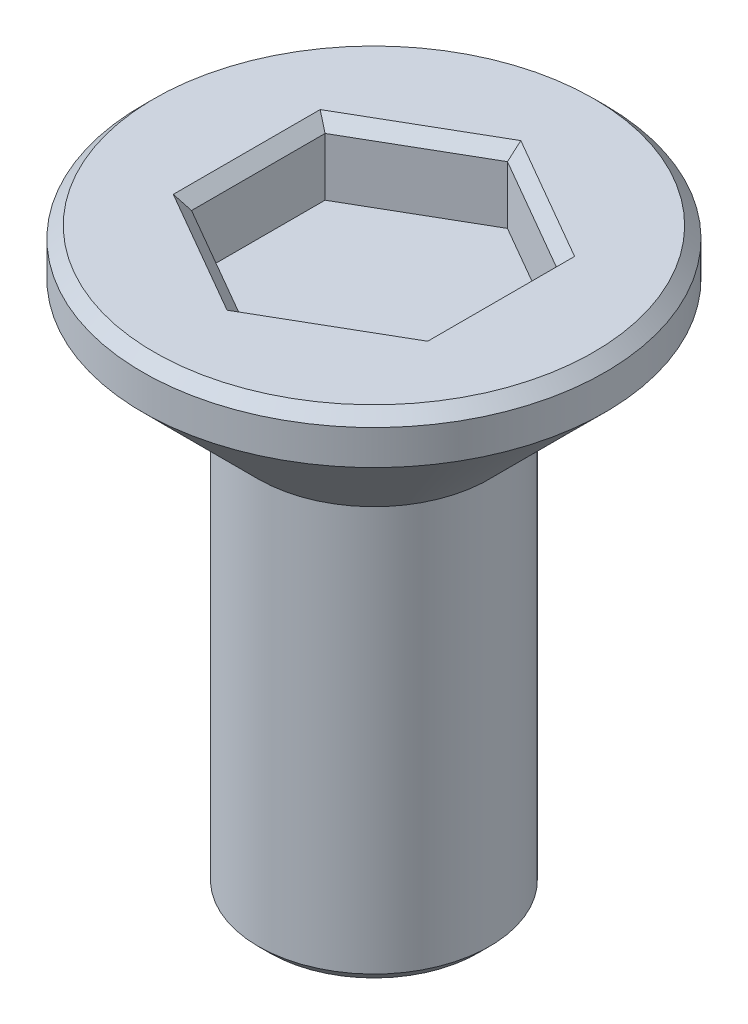
SolidWorks part; units mm, degrees
material "Plain Carbon Steel"
ref_plane "Front Plane" through (0, 0, 0) normal (0, 0, 1) x (1, 0, 0)
ref_plane "Top Plane" through (0, 0, 0) normal (0, 1, 0) x (1, 0, 0)
ref_plane "Right Plane" through (0, 0, 0) normal (1, 0, 0) x (0, 0, -1)
sketch "Sketch1" plane through (0, 0, 0) normal (1, 0, 0) x (0, 0, -1)
  line L0 (0, 0) -> (0, 5) construction
  line L1 (0, 5) -> (-2, 5)
  line L3 (-1, 3.6) -> (-1, 0)
  line L4 (-1, 0) -> (0, 0)
  line L5 (0, 0) -> (0, 5)
  line L6 (-2, 4.6) -> (-1, 3.6)
  line L7 (-2, 4.6) -> (-2, 5)
  point P3 (-0.5, 0)
  dimension "D1" = 5
  dimension "D2" = 1
  dimension "D3" = 2
  dimension "D4" = 1.4
  dimension "D5" = 45
revolve "Revolve1" add sketch "Sketch1" angle 360 about L0
sketch "Sketch2" plane through (0, 5, 0) normal (0, 1, 0) x (1, 0, 0)
  line L1 (0, -1.1547) -> (1, -0.5774)
  line L2 (1, -0.5774) -> (1, 0.5774)
  line L3 (1, 0.5774) -> (0, 1.1547)
  line L4 (0, 1.1547) -> (-1, 0.5774)
  line L5 (-1, 0.5774) -> (-1, -0.5774)
  line L6 (-1, -0.5774) -> (0, -1.1547)
  circle A0 centre (0, 0) radius 1 construction
  dimension "D1" = 2
extrude "Cut-Extrude1" cut sketch "Sketch2" against normal blind 0.6
chamfer "Chamfer1" distance 0.1 angle 45 1 edges at (0, 0, -1)
chamfer "Chamfer2" distance 0.1 angle 45 7 edges at (-0.5, 5, 0.866) (0.5, 5, 0.866) (1, 5, 0) (0.5, 5, -0.866) (-0.5, 5, -0.866) (-1, 5, 0) (0, 5, -2)
